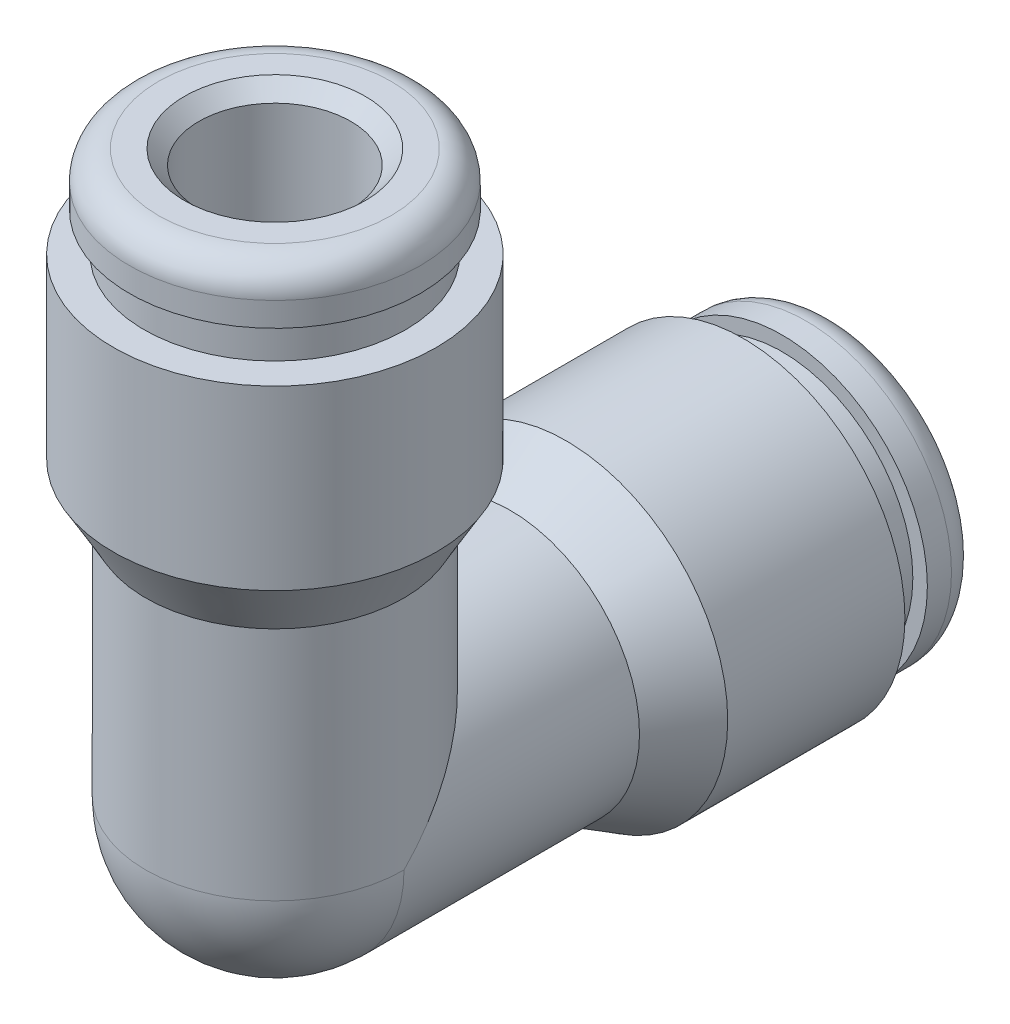
SolidWorks part; units mm, degrees
ref_plane "Front Plane" through (0, 0, 0) normal (0, 0, 1) x (1, 0, 0)
ref_plane "Top Plane" through (0, 0, 0) normal (0, 1, 0) x (1, 0, 0)
ref_plane "Right Plane" through (0, 0, 0) normal (1, 0, 0) x (0, 0, -1)
sketch "Sketch1" plane through (0, 0, 0) normal (1, 0, 0) x (0, 0, -1)
  line L0 (13.353, 3.825) -> (13.988, 3.825)
  line L1 (7.6722, 4.25) -> (12.337, 4.25)
  line L2 (0, 3.4) -> (0, 1.238)
  line L3 (5.25, 2) -> (14.369, 2)
  line L4 (14.75, 3.063) -> (14.75, 2.381)
  line L5 (0, 0) -> (0, 14.75) construction
  line L6 (12.337, 4.25) -> (12.337, 3.4425)
  line L7 (12.337, 3.4425) -> (13.353, 3.4425)
  line L8 (13.353, 3.825) -> (13.353, 3.4425)
  line L9 (-4.25, 14.75) -> (4.25, 14.75) construction
  line L10 (0, 0) -> (14.75, 0) construction
  line L11 (5.25, 2) -> (5.25, 1.238)
  line L12 (14.369, 2) -> (14.75, 2.381)
  line L13 (0, 0) -> (0, 1.238) construction
  line L14 (0, 3.4) -> (6.2, 3.4)
  line L15 (6.2, 3.4) -> (7.6722, 4.25)
  line L16 (5.25, 1.238) -> (0, 1.238)
  arc A0 (13.988, 3.825) -> (14.75, 3.063) centre (13.988, 3.063) cw
  point P1 (14.75, 2)
  point P20 (14.75, 3.825)
  dimension "D4" = 0.762
  dimension "tube od" = 4
  dimension "D1" = 1.397
  dimension "D2" = 1.016
  dimension "D3" = 6.885
  dimension "D6" = 7.65
  dimension "D9" = 30
  dimension "D10" = 6.8
  dimension "D5" = 8.55
  dimension "D8" = 8.5
  dimension "D11" = 0.762
revolve "Revolve1" add sketch "Sketch1" angle 360 about L10
ref_axis "Axis1" through (-4.675, 0, 0) along (1, 0, 0)
pattern_circular "CirPattern1" count 2 over 90 about axis through (-4.675, 0, 0) along (1, 0, 0) of bodies 118 123
sketch "Sketch2" plane through (0, 0, 0) normal (0, 0, 1) x (1, 0, 0)
  line L0 (-3.4, 0) -> (-1.238, 0)
  line L1 (-3.4, 0) -> (3.4, 0) construction
  line L2 (1.238, 0) -> (3.4, 0)
  arc A0 (-3.4, 0) -> (3.4, 0) centre (0, 0) ccw
  arc A2 (-1.238, 0) -> (1.238, 0) centre (0, 0) ccw
  circle A4 centre (0, 0) radius 1.238 construction
  circle A5 centre (0, 0) radius 3.4 construction
revolve "Revolve2" add sketch "Sketch2" angle 90 about L1
combine bodies "Combine1" operation type add bodies to combine 122 124
sketch "Sketch3" plane through (0, 0, 0) normal (1, 0, 0) x (0, 0, -1)
  line L0 (14.75, 2.381) -> (14.369, 2)
  line L1 (14.369, 2) -> (5.25, 2)
  line L2 (5.25, 2) -> (5.25, 1.238)
  line L3 (5.25, 1.238) -> (0, 1.238)
  line L4 (0, 1.238) -> (0, 0)
  line L5 (0, 0) -> (14.75, 0)
  line L6 (14.75, 0) -> (14.75, 2.381)
revolve "Cut-Revolve1" cut sketch "Sketch3" angle 360 about L5
pattern_circular "CirPattern2" count 2 over 90 about axis through (-4.675, 0, 0) along (1, 0, 0) of "Cut-Revolve1"
equation "\"D6@Sketch1\" = \"G@Sketch1\"*.9"
equation "\"D3@Sketch1\" = \"D6@Sketch1\"*.9"
equation "\"D10@Sketch1\" = \"G@Sketch1\"*.8"
equation "\"D5@Sketch1\" = \"L@Sketch1\"*.45"
equation "\"D8@Sketch1\" = \"G@Sketch1\""
